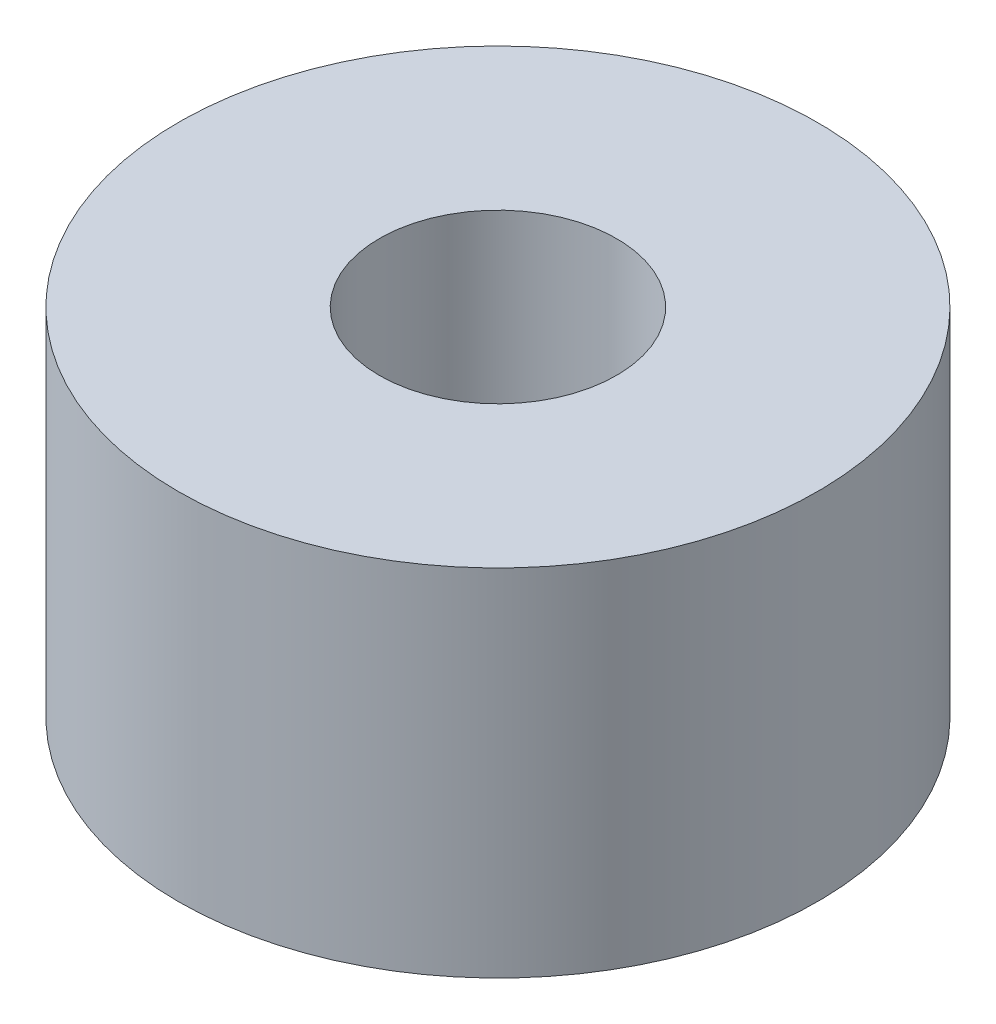
SolidWorks part; units mm, degrees
material "ABS"
ref_plane "Front Plane" through (0, 0, 0) normal (0, 0, 1) x (1, 0, 0)
ref_plane "Top Plane" through (0, 0, 0) normal (0, 1, 0) x (1, 0, 0)
ref_plane "Right Plane" through (0, 0, 0) normal (1, 0, 0) x (0, 0, -1)
sketch "Sketch1" plane through (0, 0, 0) normal (0, 1, 0) x (1, 0, 0)
  circle A0 centre (0, 0) radius 2.1209
  circle A1 centre (0, 0) radius 5.715
  dimension "D1" = 4.2418
  dimension "D2" = 11.43
extrude "Boss-Extrude1" add sketch "Sketch1" along normal blind 6.35
